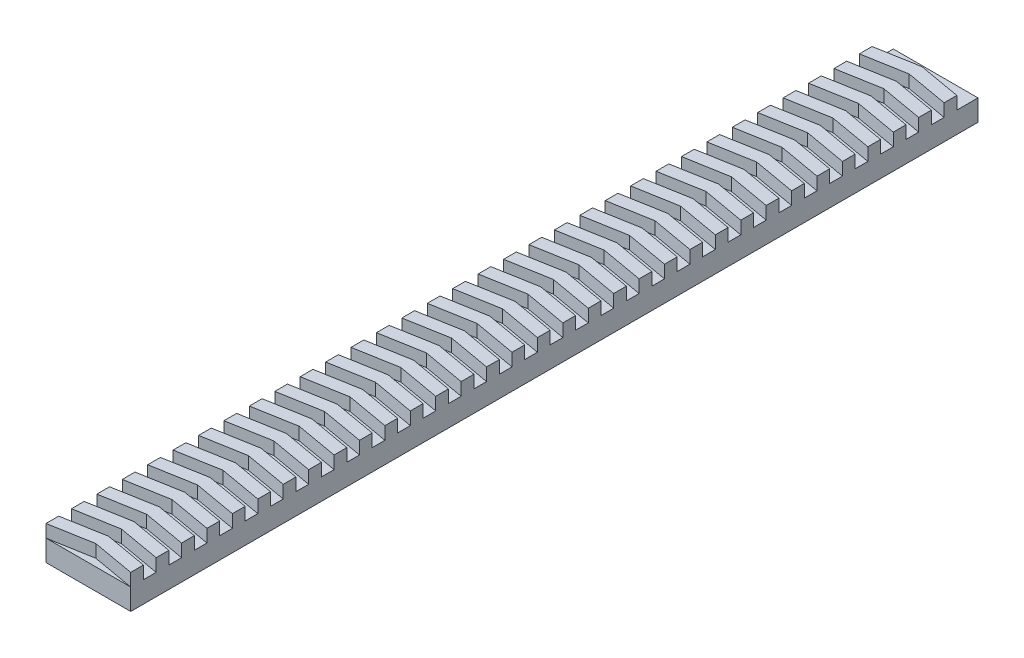
SolidWorks part; units mm, degrees
ref_plane "Front Plane" through (0, 0, 0) normal (0, 0, 1) x (1, 0, 0)
ref_plane "Top Plane" through (0, 0, 0) normal (0, 1, 0) x (1, 0, 0)
ref_plane "Right Plane" through (0, 0, 0) normal (1, 0, 0) x (0, 0, -1)
sketch "Sketch2" plane through (0, 0, 0) normal (0, 1, 0) x (1, 0, 0)
  line L1 (-10, -100) -> (10, -100)
  line L2 (-10, -100) -> (-10, 100)
  line L3 (-10, 100) -> (10, 100)
  line L4 (10, -100) -> (10, 100)
  line L5 (-10, -100) -> (10, 100) construction
  line L6 (-10, 100) -> (10, -100) construction
  point P0 (0, 0)
  dimension "D1" = 200
  dimension "D2" = 20
extrude "Boss-Extrude1" add sketch "Sketch2" along normal blind 5
sketch "Sketch3" plane through (0, 5, 0) normal (0, 1, 0) x (1, 0, 0)
  line L0 (0, -100) -> (0, 100) construction
  line L1 (-10, -100) -> (10, -100) construction
  line L2 (10, 100) -> (-10, 100) construction
  line L3 (-10, -100) -> (0, -98.2367)
  line L4 (0, -98.2367) -> (10, -100)
  line L5 (0, -95.2367) -> (-10, -97)
  line L6 (-10, 100) -> (-10, -100) construction
  line L7 (0, -95.2367) -> (10, -97)
  line L8 (10, -100) -> (10, 100) construction
  line L9 (-10, -97) -> (-10, -100)
  line L10 (10, -97) -> (10, -100)
  point P9 (0, -95.2367)
  dimension "D1" = 10
  dimension "D2" = 3
extrude "Boss-Extrude2" add sketch "Sketch3" along normal blind 3
sketch "Sketch4" plane through (-10, 0, 0) normal (-1, 0, 0) x (0, 0, 1)
  line L0 (97, 8) -> (100, 8) construction
  line L1 (97, 8) -> (97, 5) construction
  line L2 (100, 8) -> (100, 5) construction
  line L3 (97, 6.5) -> (100, 6.5) construction
  line L4 (98.5, 8) -> (98.5, 4.9346) construction
  line L5 (97.75, 8) -> (97, 8)
  line L6 (97, 8) -> (97, 5)
  line L7 (99.25, 8) -> (100, 8)
  line L8 (100, 8) -> (100, 5)
  spline S0 degree 2 poles (97.75, 8) (96.9504, 6.6039) (97, 5) knots 0 0 0 1 1 1
  spline S1 degree 2 poles (99.25, 8) (100.0496, 6.6039) (100, 5) knots 0 0 0 1 1 1
  point P0 (97.75, 8)
  point P10 (97.15, 6.5)
  dimension "D1" = 0.75
  dimension "D3" = 0.15
pattern_linear "LPattern1" count 33 spacing 6 along (0, 0, -1) of "Boss-Extrude2"
